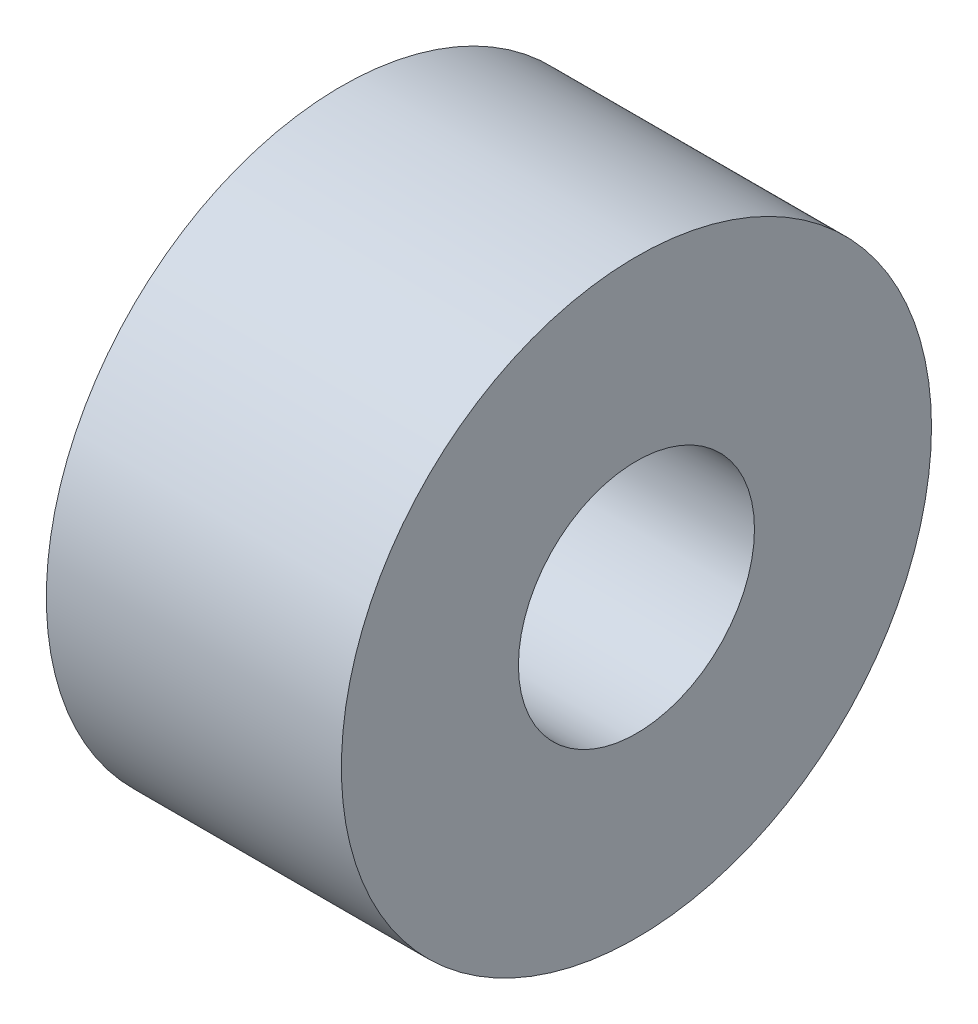
SolidWorks part; units mm, degrees
ref_plane "Спереди" through (0, 0, 0) normal (0, 0, 1) x (1, 0, 0)
ref_plane "Сверху" through (0, 0, 0) normal (0, 1, 0) x (1, 0, 0)
ref_plane "Справа" through (0, 0, 0) normal (1, 0, 0) x (0, 0, -1)
sketch "Эскиз1" plane through (0, 0, 0) normal (1, 0, 0) x (0, 0, -1)
  circle A0 centre (0, 0) radius 4
  circle A1 centre (0, 0) radius 10
extrude "Вытянуть1" add sketch "Эскиз1" along normal blind 10
